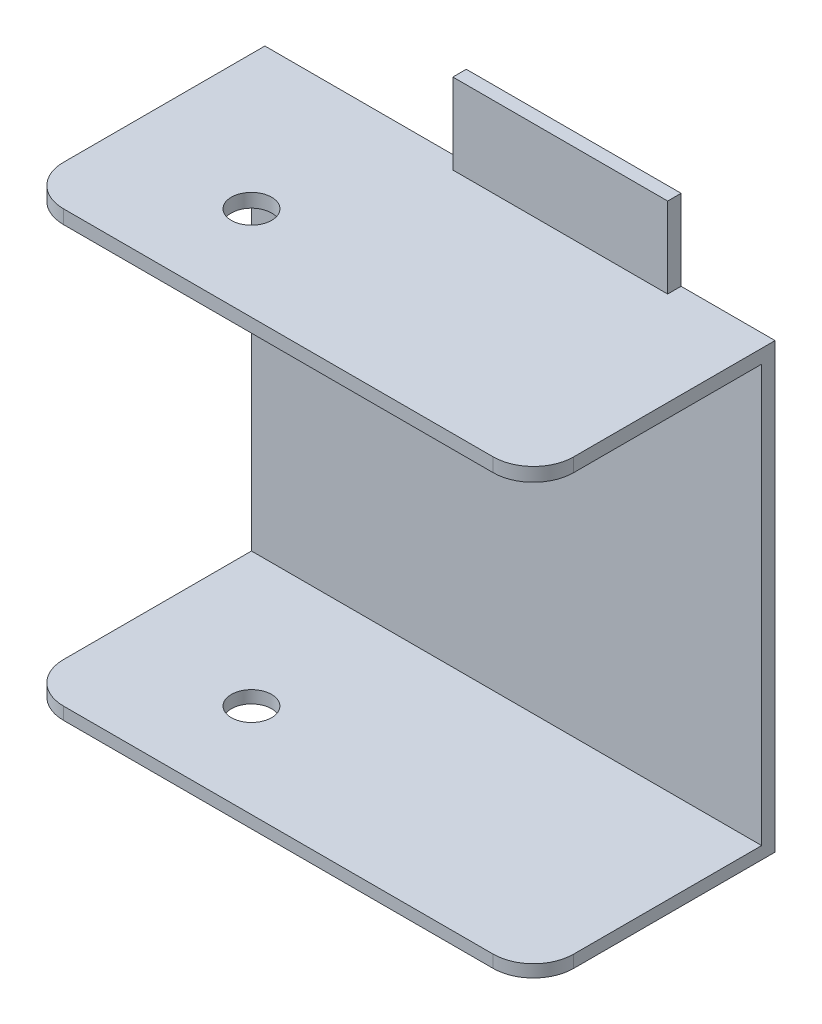
SolidWorks part; units mm, degrees
ref_plane "Plan de face" through (0, 0, 0) normal (0, 0, 1) x (1, 0, 0)
ref_plane "Plan de dessus" through (0, 0, 0) normal (0, 1, 0) x (1, 0, 0)
ref_plane "Plan de droite" through (0, 0, 0) normal (1, 0, 0) x (0, 0, -1)
sketch "Esquisse1" plane through (0, 0, 0) normal (0, 0, 1) x (1, 0, 0)
  line L0 (-30.9892, 10.739) -> (-30.9892, -22.261)
  line L1 (-77.8035, -5.761) -> (7.1636, -5.761) construction
  line L2 (-68.9892, 10.739) -> (-68.9892, -22.261)
  line L3 (-53.9892, 16.739) -> (-37.9892, 16.739)
  line L8 (-68.9892, 10.739) -> (-53.9892, 10.739)
  line L9 (-53.9892, -22.261) -> (-68.9892, -22.261)
  line L10 (-53.9892, 16.739) -> (-53.9892, 10.739)
  line L11 (-37.9892, -22.261) -> (-30.9892, -22.261)
  line L12 (-37.9892, 16.739) -> (-37.9892, 10.739)
  line L13 (-37.9892, -28.261) -> (-37.9892, -22.261)
  line L14 (-53.9892, -28.261) -> (-53.9892, -22.261)
  line L15 (-53.9892, -28.261) -> (-37.9892, -28.261)
  line L16 (-37.9892, 10.739) -> (-30.9892, 10.739)
  dimension "D6" = 16
  dimension "D7" = 6
  dimension "D9" = 16.5
extrude "Extrusion1" add sketch "Esquisse1" along normal blind 1
sketch "Esquisse14" plane through (0, 0, 1) normal (0, 0, 1) x (1, 0, 0)
  line L1 (-68.9892, 10.739) -> (-30.9892, 10.739)
  line L2 (-68.9892, 10.739) -> (-68.9892, 9.7177)
  line L3 (-68.9892, 9.7177) -> (-30.9892, 9.7177)
  line L4 (-30.9892, 10.739) -> (-30.9892, 9.7177)
  line L6 (-68.9892, -22.261) -> (-30.9892, -22.261)
  line L7 (-68.9892, -22.261) -> (-68.9892, -21.3365)
  line L8 (-68.9892, -21.3365) -> (-30.9892, -21.3365)
  line L9 (-30.9892, -22.261) -> (-30.9892, -21.3365)
extrude "Extrusion2" add sketch "Esquisse14" along normal blind 17
fillet "Congé3" radius 3 4 edges at (-68.9892, -21.7987, 18) (-30.9892, -21.7987, 18) (-30.9892, 10.2284, 18) (-68.9892, 10.2284, 18)
sketch "Esquisse20" plane through (0, 10.739, 0) normal (0, 1, 0) x (-1, 0, 0)
  line L0 (53.9892, 0) -> (68.9892, 0) construction
  line L3 (68.9892, 15) -> (68.9892, 0) construction
  circle A0 centre (109.6643, 11.5857) radius 1.5517
  circle A1 centre (58.9892, 11) radius 1.5
  dimension "D2" = 10
  dimension "D4" = 3
  dimension "D1" = 11
extrude "Enlèv. mat.-Extru.7" cut sketch "Esquisse20" against normal blind 46
